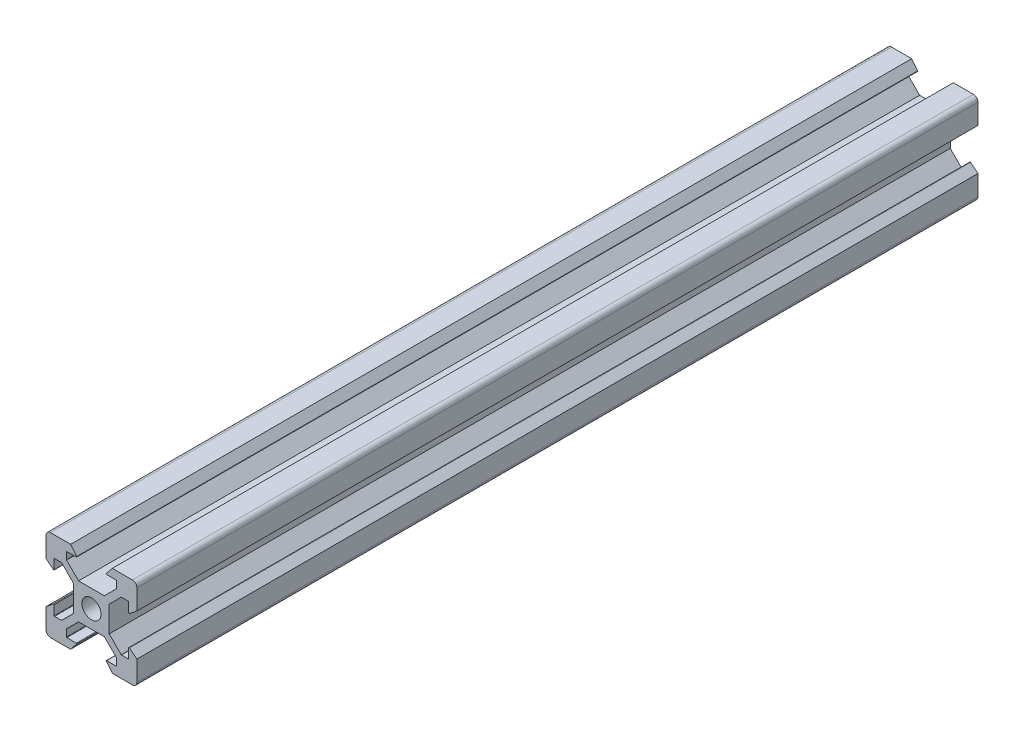
SolidWorks part; units mm, degrees
ref_plane "Front Plane" through (0, 0, 0) normal (0, 0, 1) x (1, 0, 0)
ref_plane "Top Plane" through (0, 0, 0) normal (0, 1, 0) x (1, 0, 0)
ref_plane "Right Plane" through (0, 0, 0) normal (1, 0, 0) x (0, 0, -1)
sketch "Sketch1" plane through (0, 0, 0) normal (0, 0, 1) x (1, 0, 0)
  line L0 (-2.8393, 3.9) -> (-5.4707, 6.5314)
  line L1 (-10, 10) -> (-4.58, 10)
  line L2 (-10, 10) -> (-10, 4.58)
  line L3 (-10, -10) -> (-4.58, -10)
  line L4 (10, 10) -> (10, 4.58)
  line L5 (-10, 10) -> (-3.9, 3.9) construction
  line L6 (-10, -10) -> (-4.061, -4.061) construction
  line L7 (-2.8393, 3.9) -> (2.8393, 3.9)
  line L8 (-3.9, 2.8393) -> (-3.9, -2.8393)
  line L9 (-2.8393, -3.9) -> (2.8393, -3.9)
  line L10 (3.9, 2.8393) -> (3.9, -2.8393)
  line L11 (-1.4849, 1.4849) -> (3.9, -3.9) construction
  line L12 (-3.9, -3.9) -> (1.4849, 1.4849) construction
  line L13 (-5.5, 6.6021) -> (-5.5, 8.1)
  line L14 (-5.4, 8.2) -> (-3.3344, 8.2)
  line L15 (-3.2566, 8.3629) -> (-4.58, 10)
  line L16 (0, 0) -> (0, 5.2663) construction
  line L17 (-3.9, 2.8393) -> (-6.5314, 5.4707)
  line L18 (-6.6021, 5.5) -> (-8.1, 5.5)
  line L19 (-8.2, 5.4) -> (-8.2, 3.3344)
  line L20 (-8.3629, 3.2566) -> (-10, 4.58)
  line L21 (8.3629, 3.2566) -> (10, 4.58)
  line L22 (8.2, 5.4) -> (8.2, 3.3344)
  line L23 (6.6021, 5.5) -> (8.1, 5.5)
  line L24 (3.9, 2.8393) -> (6.5314, 5.4707)
  line L25 (3.2566, 8.3629) -> (4.58, 10)
  line L26 (5.4, 8.2) -> (3.3344, 8.2)
  line L27 (2.8393, 3.9) -> (5.4707, 6.5314)
  line L28 (5.5, 6.6021) -> (5.5, 8.1)
  line L29 (55, 0) -> (-55, 0) construction
  line L30 (-8.3629, -3.2566) -> (-10, -4.58)
  line L31 (-8.2, -5.4) -> (-8.2, -3.3344)
  line L32 (-6.6021, -5.5) -> (-8.1, -5.5)
  line L33 (-3.9, -2.8393) -> (-6.5314, -5.4707)
  line L34 (-2.8393, -3.9) -> (-5.4707, -6.5314)
  line L35 (-5.5, -6.6021) -> (-5.5, -8.1)
  line L36 (-5.4, -8.2) -> (-3.3344, -8.2)
  line L37 (-3.2566, -8.3629) -> (-4.58, -10)
  line L38 (8.3629, -3.2566) -> (10, -4.58)
  line L39 (8.2, -5.4) -> (8.2, -3.3344)
  line L40 (6.6021, -5.5) -> (8.1, -5.5)
  line L41 (3.9, -2.8393) -> (6.5314, -5.4707)
  line L42 (2.8393, -3.9) -> (5.4707, -6.5314)
  line L43 (5.5, -6.6021) -> (5.5, -8.1)
  line L44 (5.4, -8.2) -> (3.3344, -8.2)
  line L45 (3.2566, -8.3629) -> (4.58, -10)
  line L46 (3.9, 3.9) -> (10, 10) construction
  line L47 (3.2459, -3.2459) -> (10, -10) construction
  line L48 (-10, -4.58) -> (-10, -10)
  line L49 (4.58, -10) -> (10, -10)
  line L50 (10, -4.58) -> (10, -10)
  line L51 (4.58, 10) -> (10, 10)
  circle A0 centre (0, 0) radius 2.1
  arc A1 (-5.4707, 6.5314) -> (-5.5, 6.6021) centre (-5.4, 6.6021) cw
  arc A2 (-5.5, 8.1) -> (-5.4, 8.2) centre (-5.4, 8.1) cw
  arc A3 (-3.3344, 8.2) -> (-3.2566, 8.3629) centre (-3.3344, 8.3) ccw
  arc A4 (-6.5314, 5.4707) -> (-6.6021, 5.5) centre (-6.6021, 5.4) ccw
  arc A5 (-8.1, 5.5) -> (-8.2, 5.4) centre (-8.1, 5.4) ccw
  arc A6 (-8.2, 3.3344) -> (-8.3629, 3.2566) centre (-8.3, 3.3344) cw
  arc A7 (8.2, 3.3344) -> (8.3629, 3.2566) centre (8.3, 3.3344) ccw
  arc A8 (8.1, 5.5) -> (8.2, 5.4) centre (8.1, 5.4) cw
  arc A9 (6.5314, 5.4707) -> (6.6021, 5.5) centre (6.6021, 5.4) cw
  arc A10 (3.3344, 8.2) -> (3.2566, 8.3629) centre (3.3344, 8.3) cw
  arc A11 (5.5, 8.1) -> (5.4, 8.2) centre (5.4, 8.1) ccw
  arc A12 (5.4707, 6.5314) -> (5.5, 6.6021) centre (5.4, 6.6021) ccw
  arc A13 (-8.2, -3.3344) -> (-8.3629, -3.2566) centre (-8.3, -3.3344) ccw
  arc A14 (-8.1, -5.5) -> (-8.2, -5.4) centre (-8.1, -5.4) cw
  arc A15 (-6.5314, -5.4707) -> (-6.6021, -5.5) centre (-6.6021, -5.4) cw
  arc A16 (-5.4707, -6.5314) -> (-5.5, -6.6021) centre (-5.4, -6.6021) ccw
  arc A17 (-5.5, -8.1) -> (-5.4, -8.2) centre (-5.4, -8.1) ccw
  arc A18 (-3.3344, -8.2) -> (-3.2566, -8.3629) centre (-3.3344, -8.3) cw
  arc A19 (8.2, -3.3344) -> (8.3629, -3.2566) centre (8.3, -3.3344) cw
  arc A20 (8.1, -5.5) -> (8.2, -5.4) centre (8.1, -5.4) ccw
  arc A21 (6.5314, -5.4707) -> (6.6021, -5.5) centre (6.6021, -5.4) ccw
  arc A22 (5.4707, -6.5314) -> (5.5, -6.6021) centre (5.4, -6.6021) cw
  arc A23 (5.5, -8.1) -> (5.4, -8.2) centre (5.4, -8.1) cw
  arc A24 (3.3344, -8.2) -> (3.2566, -8.3629) centre (3.3344, -8.3) ccw
  point P0 (0, 0)
  point P6 (0, 0)
  point P25 (-3.125, 8.2)
  dimension "D5" = 4.2
  dimension "D11" = 0.1
  dimension "D1" = 20
  dimension "D3" = 7.8
  dimension "D4" = 7.8
  dimension "D6" = 0.75
  dimension "D7" = 4.3
  dimension "D8" = 4.58
  dimension "D9" = 3.125
  dimension "D10" = 5.5
extrude "Boss-Extrude1" add sketch "Sketch1" along normal blind 185
fillet "Fillet1" radius 1 4 edges at (10, -10, 92.5) (10, 10, 92.5) (-10, -10, 92.5) (-10, 10, 92.5)
